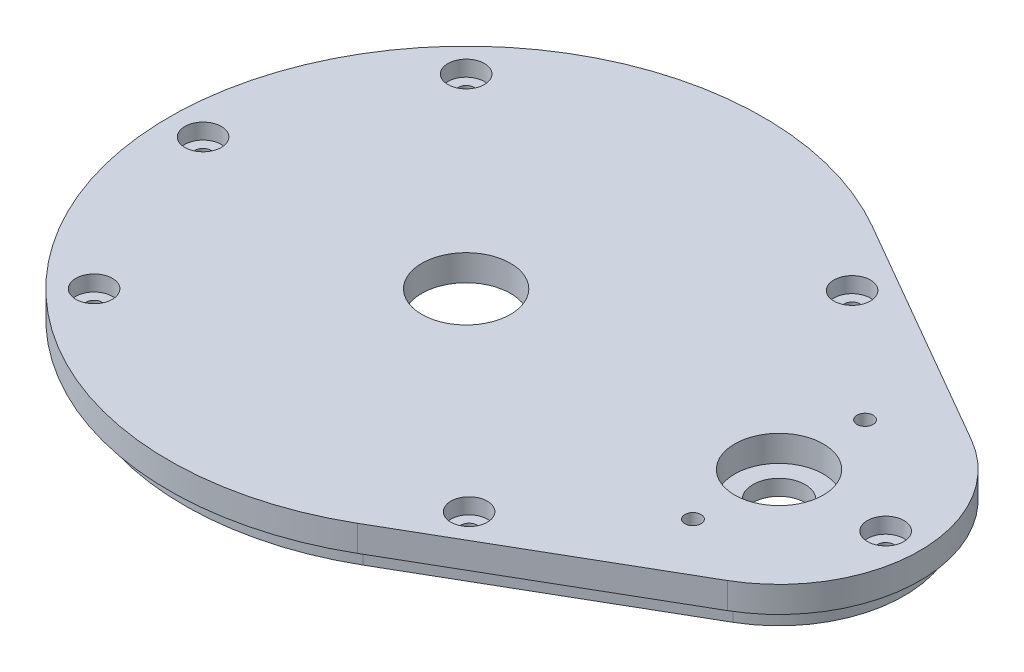
SolidWorks part; units mm, degrees
ref_plane "Front Plane" through (0, 0, 0) normal (0, 0, 1) x (1, 0, 0)
ref_plane "Top Plane" through (0, 0, 0) normal (0, 1, 0) x (1, 0, 0)
ref_plane "Right Plane" through (0, 0, 0) normal (1, 0, 0) x (0, 0, -1)
sketch "Sketch1" plane through (0, 0, 0) normal (0, 1, 0) x (1, 0, 0)
  line L8 (45, -16.5) -> (45, 16.5) construction
  line L9 (13.5, -49.3634) -> (58.5, -23.3827)
  line L10 (13.5, 49.3634) -> (58.5, 23.3827)
  circle A0 centre (-15, 0) radius 46.5 construction
  circle A1 centre (45, 0) radius 16.5 construction
  circle A2 centre (-15, 0) radius 8.5
  circle A3 centre (45, 0) radius 8.5
  circle A4 centre (45, 16.5) radius 1.55
  circle A5 centre (45, -16.5) radius 1.55
  circle A8 centre (-15, 0) radius 57 construction
  circle A9 centre (45, 0) radius 27 construction
  arc A12 (13.5, 49.3634) -> (13.5, -49.3634) centre (-15, 0) ccw
  arc A13 (58.5, 23.3827) -> (58.5, -23.3827) centre (45, 0) cw
  point P0 (0, 0)
  point P17 (45, 0)
  point P18 (45, 0)
extrude "Boss-Extrude1" add sketch "Sketch1" along normal blind 5
sketch "Sketch2" plane through (0, 0, 0) normal (0, -1, 0) x (1, 0, 0)
  circle A0 centre (45, 0) radius 5
  circle A1 centre (45, 0) radius 12
extrude "Boss-Extrude2" add sketch "Sketch2" along normal blind 3
sketch "Sketch4" plane through (0, 0, 0) normal (0, -1, 0) x (1, 0, 0)
  line L0 (12, 46.7654) -> (57, 20.7846)
  line L1 (12, -46.7654) -> (57, -20.7846)
  line L3 (11, -45.0333) -> (56, -19.0526)
  line L4 (11, 45.0333) -> (56, 19.0526)
  circle A0 centre (-15, 0) radius 54 construction
  circle A1 centre (45, 0) radius 24 construction
  arc A2 (12, 46.7654) -> (12, -46.7654) centre (-15, 0) ccw
  arc A3 (57, 20.7846) -> (57, -20.7846) centre (45, 0) cw
  circle A4 centre (-15, 0) radius 52 construction
  circle A5 centre (45, 0) radius 22 construction
  arc A8 (56, -19.0526) -> (56, 19.0526) centre (45, 0) ccw
  arc A9 (11, -45.0333) -> (11, 45.0333) centre (-15, 0) cw
extrude "Boss-Extrude3" add sketch "Sketch4" along normal blind 4
sketch "Sketch5" plane through (0, 5, 0) normal (0, 1, 0) x (1, 0, 0)
  line L0 (-67, 0) -> (-65.45, 0) construction
  line L1 (67, 0) -> (65.45, 0) construction
  line L2 (-51.9706, -36.9706) -> (21.9706, 36.9706) construction
  line L3 (-15, 0) -> (-51.7696, 36.7696) construction
  line L4 (-51.7696, -36.7696) -> (-50.6735, -35.6735) construction
  line L5 (23.0666, -38.0666) -> (22.2916, -36.7243) construction
  line L6 (11, 45.0333) -> (56, 19.0526) construction
  line L7 (-51.7696, 36.7696) -> (-50.6735, 35.6735) construction
  line L8 (11, -45.0333) -> (56, -19.0526) construction
  line L10 (23.0666, 38.0666) -> (22.2847, 36.7283) construction
  line L11 (-15, 0) -> (45, 0) construction
  arc A17 (11, 45.0333) -> (11, -45.0333) centre (-15, 0) ccw construction
  circle A18 centre (-65.45, 0) radius 1.55
  arc A20 (56, -19.0526) -> (56, 19.0526) centre (45, 0) ccw construction
  circle A21 centre (65.45, 0) radius 1.55
  circle A29 centre (-50.6735, -35.6735) radius 1.55
  circle A33 centre (22.2847, 36.7283) radius 1.55
  circle A35 centre (22.2916, -36.7243) radius 1.55
  circle A36 centre (-50.6735, 35.6735) radius 1.55
  point P39 (-15, 0)
extrude "Cut-Extrude1" cut sketch "Sketch5" against normal blind 5
sketch "Sketch6" plane through (0, 5, 0) normal (0, 1, 0) x (1, 0, 0)
  circle A0 centre (-50.6735, 35.6735) radius 3.5
  circle A1 centre (-65.45, 0) radius 3.5
  circle A2 centre (-50.6735, -35.6735) radius 3.5
  circle A3 centre (22.2916, -36.7243) radius 3.5
  circle A4 centre (22.2847, 36.7283) radius 3.5
  circle A5 centre (65.45, 0) radius 3.5
extrude "Cut-Extrude2" cut sketch "Sketch6" against normal blind 3
